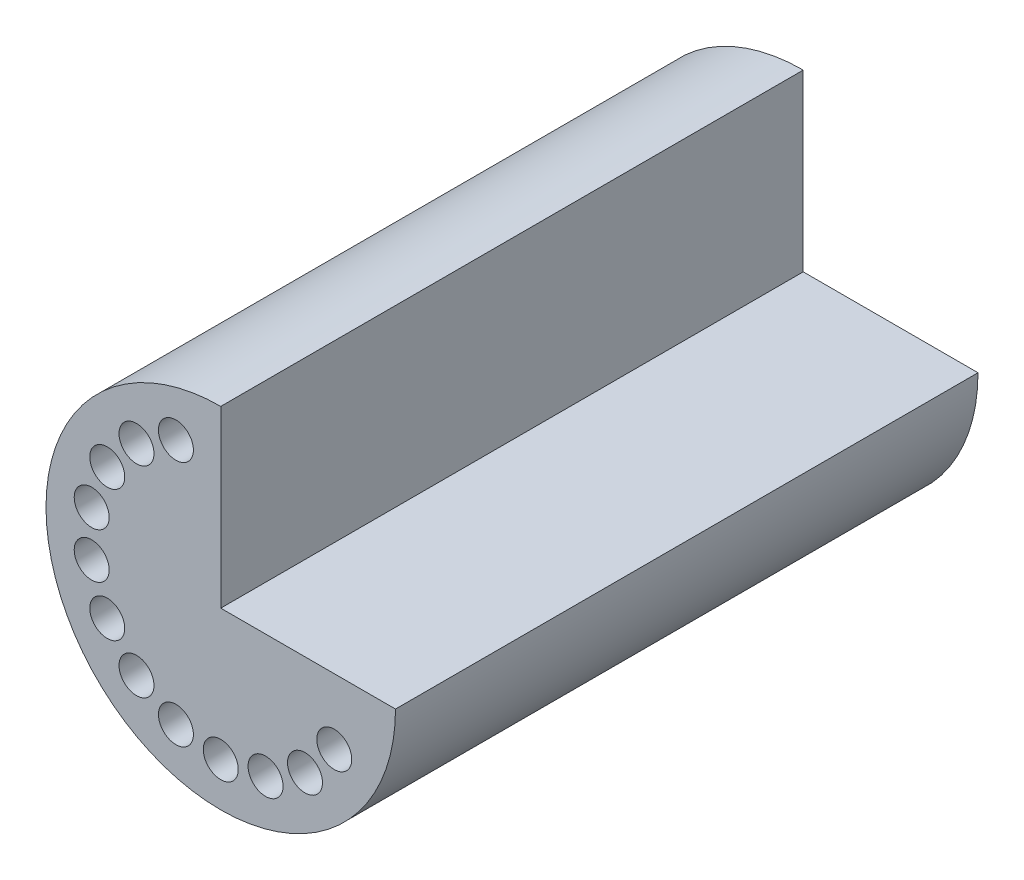
SolidWorks part; units mm, degrees
material "AISI 1020"
ref_plane "Front Plane" through (0, 0, 0) normal (0, 0, 1) x (1, 0, 0)
ref_plane "Top Plane" through (0, 0, 0) normal (0, 1, 0) x (1, 0, 0)
ref_plane "Right Plane" through (0, 0, 0) normal (1, 0, 0) x (0, 0, -1)
sketch "Sketch1" plane through (0, 0, 0) normal (0, 0, 1) x (1, 0, 0)
  circle A0 centre (0, 0) radius 150
  dimension "D1" = 300
extrude "Boss-Extrude1" add sketch "Sketch1" against normal blind 500
sketch "Sketch2" plane through (0, 0, 0) normal (0, 0, 1) x (1, 0, 0)
  line L1 (0, 0) -> (150, 0)
  line L2 (0, 0) -> (0, 150)
  line L3 (0, 150) -> (150, 150)
  line L4 (150, 0) -> (150, 150)
  circle A0 centre (0, 0) radius 150 construction
extrude "Cut-Extrude1" cut sketch "Sketch2" against normal through all
sketch "Sketch3" plane through (0, 0, 0) normal (0, 0, 1) x (1, 0, 0)
  line L0 (0, 0) -> (-38.4773, 105.7154) construction
  line L1 (0, 150) -> (0, 0) construction
  circle A0 centre (-38.4773, 105.7154) radius 15
  circle A1 centre (0, 0) radius 112.5 construction
  dimension "D1" = 225
  dimension "D3" = 30
  dimension "D2" = 20
extrude "Cut-Extrude2" cut sketch "Sketch3" against normal through all
pattern_circular "CirPattern1" count 12 every 20 about axis through (0, 0, 0) along (0, 0, 1) of "Cut-Extrude2"
